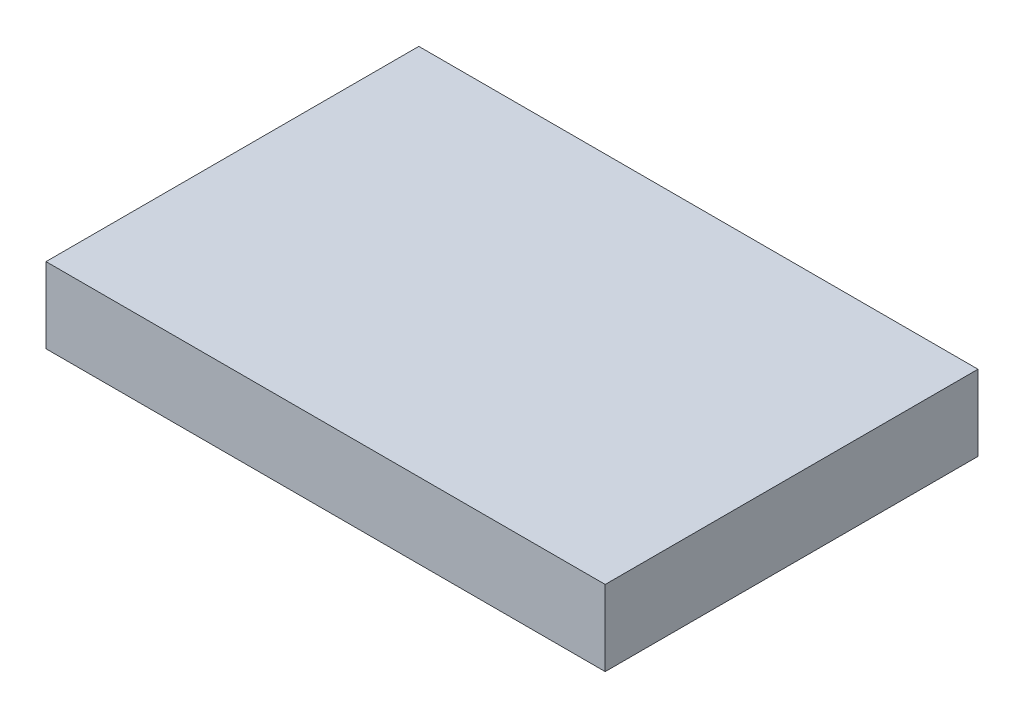
SolidWorks part; units mm, degrees
ref_plane "Front Plane" through (0, 0, 0) normal (0, 0, 1) x (1, 0, 0)
ref_plane "Top Plane" through (0, 0, 0) normal (0, 1, 0) x (1, 0, 0)
ref_plane "Right Plane" through (0, 0, 0) normal (1, 0, 0) x (0, 0, -1)
sketch "Sketch1" plane through (0, 0, 0) normal (0, 1, 0) x (1, 0, 0)
  line L1 (0, 0) -> (23.7, 0)
  line L2 (0, 0) -> (0, 15.8)
  line L3 (0, 15.8) -> (23.7, 15.8)
  line L4 (23.7, 0) -> (23.7, 15.8)
  dimension "D1" = 23.7
  dimension "D2" = 15.8
extrude "Boss-Extrude1" add sketch "Sketch1" along normal blind 3.2
